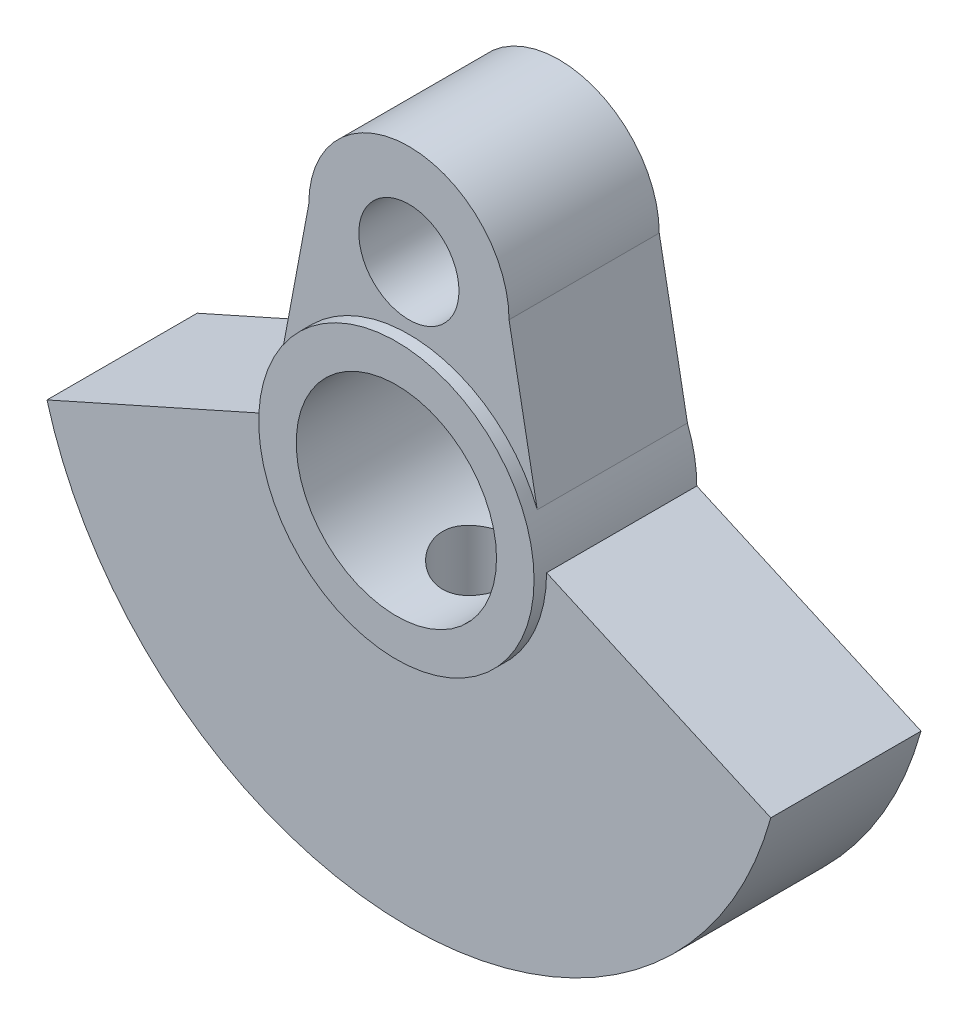
SolidWorks part; units mm, degrees
ref_plane "Front Plane" through (0, 0, 0) normal (0, 0, 1) x (1, 0, 0)
ref_plane "Top Plane" through (0, 0, 0) normal (0, 1, 0) x (1, 0, 0)
ref_plane "Right Plane" through (0, 0, 0) normal (1, 0, 0) x (0, 0, -1)
sketch "Sketch1" plane through (0, 0, 0) normal (0, 0, 1) x (1, 0, 0)
  line L0 (0, 0) -> (0, 8) construction
  line L1 (-14.4568, -4) -> (-5.5, 0)
  line L2 (5.5, 0) -> (14.4568, -4)
  line L3 (-4, 8) -> (-5.1264, 1.9925)
  line L4 (4, 8) -> (5.1264, 1.9925)
  line L5 (5.1264, 1.9925) -> (5.5, 0) construction
  line L6 (-5.1264, 1.9925) -> (-5.5, 0) construction
  line L7 (-4, 8) -> (4, 8) construction
  arc A0 (4, 8) -> (-4, 8) centre (0, 8) ccw
  circle A1 centre (0, 8) radius 2
  circle A2 centre (0, 0) radius 4
  arc A3 (-14.4568, -4) -> (14.4568, -4) centre (0, 0) ccw
  circle A4 centre (0, 0) radius 5.5
  dimension "D2" = 4
  dimension "D3" = 8
  dimension "D4" = 11
  dimension "D5" = 15
  dimension "D7" = 4
  dimension "D1" = 8
  dimension "D6" = 4
extrude "Boss-Extrude1" add sketch "Sketch1" along normal blind 6 contours A4 L4 A0 L3 A1 | A4 L1 A3 L2
sketch "Sketch2" plane through (0, 0, 0) normal (0, 0, 1) x (1, 0, 0)
  circle A0 centre (0, 0) radius 5.5
  circle A1 centre (0, 0) radius 4
  dimension "D1" = 8
  dimension "D2" = 11
extrude "Boss-Extrude2" add sketch "Sketch2" along normal blind 6.5
sketch "Sketch3" plane through (0, 0, 0) normal (0, 1, 0) x (1, 0, 0)
  line L0 (0, 0) -> (0, -3) construction
  point P1 (0, -3)
  point P7 (0, -3)
  dimension "D1" = 3
hole_wizard "M4 Tapped Hole1" positions "Sketch3" profile "Sketch4" tap size "M4" standard "DIN"
sketch "Sketch4" plane through (0, 0, 3) normal (1, 0, 0) x (0, 0, 1)
  line L0 (0, 0) -> (0, 21.0914)
  line L1 (0, 21.0914) -> (1.65, 20.1)
  line L2 (1.65, 20.1) -> (1.65, 0)
  line L5 (1.65, 0) -> (0, 0)
  line L10 (0, 21.0914) -> (-1.65, 20.1) construction
  line L11 (0, -6.35) -> (0, 107.95) construction
  dimension "Tap Drill Dia." = 3.3
  dimension "Tap Drill Depth" = 20.1
  dimension "Drill Angle" = 118
cosmetic thread "Hole Thread1"
